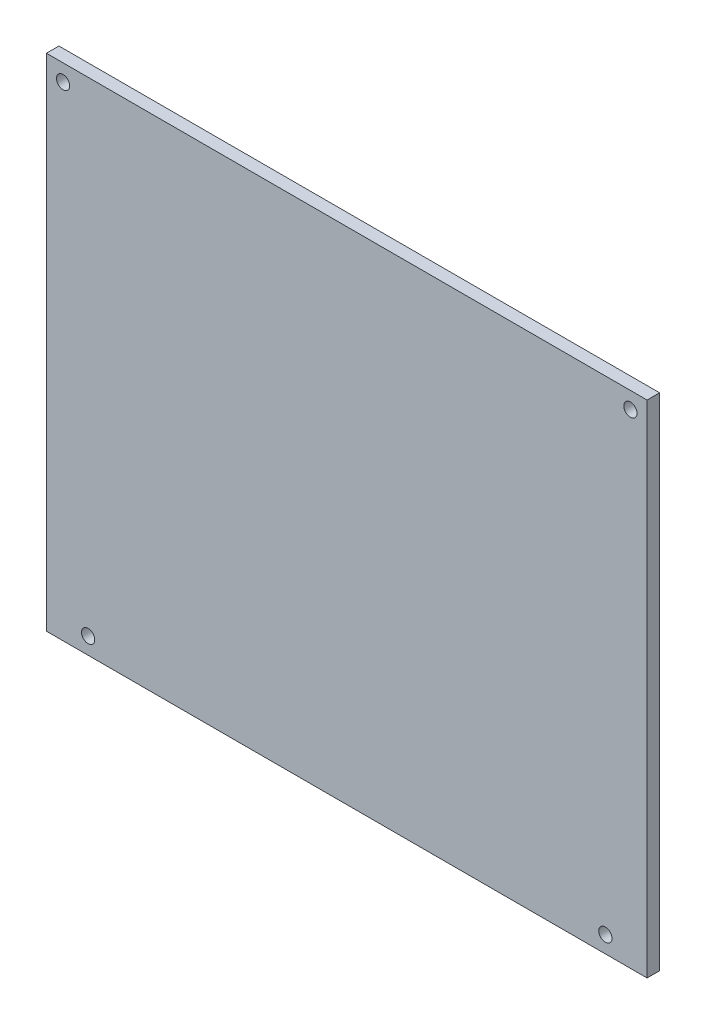
SolidWorks part; units mm, degrees
ref_plane "Front Plane" through (0, 0, 0) normal (0, 0, 1) x (1, 0, 0)
ref_plane "Top Plane" through (0, 0, 0) normal (0, 1, 0) x (1, 0, 0)
ref_plane "Right Plane" through (0, 0, 0) normal (1, 0, 0) x (0, 0, -1)
sketch "Sketch1" plane through (0, 0, 0) normal (0, 0, 1) x (1, 0, 0)
  line L0 (-228.6, -36.83) -> (-228.6, -189.23)
  line L1 (-228.6, -189.23) -> (228.6, -189.23)
  line L2 (-228.6, -189.23) -> (-228.6, 191.77) construction
  line L3 (-228.6, 191.77) -> (228.6, 191.77) construction
  line L4 (228.6, -189.23) -> (228.6, 191.77) construction
  line L5 (228.6, -36.83) -> (228.6, -189.23)
  line L8 (-228.6, -36.83) -> (-228.6, 191.77)
  line L9 (-228.6, 191.77) -> (228.6, 191.77)
  line L10 (228.6, -36.83) -> (228.6, 191.77)
  circle A0 centre (0, 0) radius 127 construction
  dimension "D1" = 254
  dimension "D4" = 189.23
  dimension "D5" = 228.6
  dimension "D2" = 457.2
  dimension "D3" = 381
extrude "Boss-Extrude1" add sketch "Sketch1" along normal blind 9.525
sketch "Sketch2" plane through (0, 0, 9.525) normal (0, 0, 1) x (1, 0, 0)
  line L0 (-228.6, 191.77) -> (-228.6, -189.23) construction
  line L2 (228.6, 191.77) -> (-228.6, 191.77) construction
  line L3 (-228.6, -189.23) -> (228.6, -189.23) construction
  line L4 (228.6, -189.23) -> (228.6, 191.77) construction
  point P0 (-215.9, 179.07)
  point P1 (215.9, 179.07)
  point P2 (196.85, -176.53)
  point P3 (-196.85, -176.53)
  dimension "D1" = 12.7
  dimension "D2" = 12.7
  dimension "D3" = 12.7
  dimension "D4" = 12.7
  dimension "D5" = 31.75
  dimension "D6" = 31.75
hole_wizard "3/8 Clearance Hole1" positions "Sketch4" profile "Sketch3" hole size "3/8" standard "ANSI Inch"
sketch "Sketch4" plane through (0, 0, 9.525) normal (0, 0, 1) x (1, 0, 0)
  point P0 (-215.9, 179.07)
  point P3 (215.9, 179.07)
  point P6 (196.85, -176.53)
  point P9 (-196.85, -176.53)
sketch "Sketch3" plane through (-215.9, 179.07, 9.525) normal (1, 0, 0) x (0, -1, 0)
  line L0 (0, 0) -> (0, 28.4295)
  line L1 (0, 28.4295) -> (5.0419, 25.4)
  line L2 (5.0419, 25.4) -> (5.0419, 0)
  line L5 (5.0419, 0) -> (0, 0)
  line L10 (0, 28.4295) -> (-5.0419, 25.4) construction
  line L11 (0, -6.35) -> (0, 107.95) construction
  dimension "Hole Dia." = 10.0838
  dimension "Hole Depth" = 25.4
  dimension "Drill Angle" = 118
